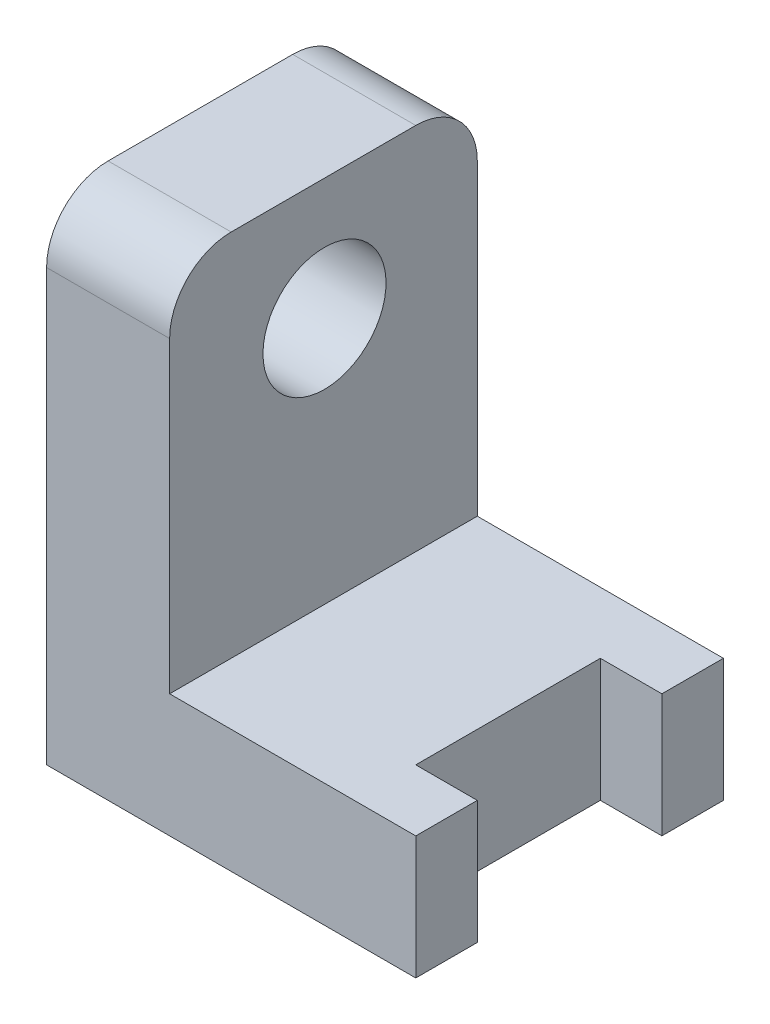
SolidWorks part; units mm, degrees
ref_plane "Piano frontale" through (0, 0, 0) normal (0, 0, 1) x (1, 0, 0)
ref_plane "Piano superiore" through (0, 0, 0) normal (0, 1, 0) x (1, 0, 0)
ref_plane "Piano destro" through (0, 0, 0) normal (1, 0, 0) x (0, 0, -1)
sketch "Schizzo1" plane through (0, 0, 0) normal (0, 0, 1) x (1, 0, 0)
  line L0 (0, 40) -> (0, 0)
  line L1 (0, 0) -> (30, 0)
  line L2 (30, 0) -> (30, 10)
  line L3 (30, 10) -> (10, 10)
  line L4 (10, 10) -> (10, 40)
  line L5 (10, 40) -> (0, 40)
  point P2 (0, 0)
  dimension "D1" = 30
  dimension "D2" = 40
  dimension "D3" = 10
  dimension "D4" = 10
extrude "Estrusione-Estrusione1" add sketch "Schizzo1" along normal mid plane 25
sketch "Schizzo3" plane through (0, 10, 0) normal (0, 1, 0) x (1, 0, 0)
  line L0 (30, 7.5) -> (25, 7.5)
  line L1 (30, -12.5) -> (30, 12.5) construction
  line L2 (25, 7.5) -> (25, -7.5)
  line L3 (25, -7.5) -> (30, -7.5)
  line L4 (30, -7.5) -> (30, 7.5)
  line L5 (0, 0) -> (25, 0) construction
  line L6 (30, 12.5) -> (10, 12.5) construction
  point P9 (0, 0)
  point P10 (25, 7.5132)
  point P15 (24.4725, 0.0815)
  dimension "D1" = 5
  dimension "D2" = 15
  dimension "D3" = 5
extrude "Taglio-Estrusione1" cut sketch "Schizzo3" against normal up to next
hole_wizard "Foro Ø10.0 (10)-1" positions "Schizzo3D3" profile "Schizzo5" hole size "Ø10.0" standard "ISO"
sketch3d "Schizzo3D3"
  line L0 (10, 40, 0) -> (10, 30, 0) construction
  line L1 (10, 40, 12.5) -> (10, 40, -12.5) construction
  line L2 (10, 30, 0) -> (10, 30, 12.5) construction
  line L3 (10, 10, 12.5) -> (10, 40, 12.5) construction
  point P1 (10, 30, 0)
  point P19 (10, 30, 0)
  point P21 (10, 30, 0)
  point P23 (0, 30.1308, -0.0834)
  dimension "D1" = 10
sketch "Schizzo5" plane through (0, 30.1308, -0.0834) normal (0, 1, 0) x (0, 0, 1)
  line L0 (0, 0) -> (0, 10.001)
  line L1 (0, 10.001) -> (5, 10.001)
  line L2 (5, 10.001) -> (5, 0)
  line L5 (5, 0) -> (0, 0)
  line L11 (0, -6.35) -> (0, 107.95) construction
  dimension "Thru Hole Dia." = 10
  dimension "Thru Hole Depth" = 10.001
fillet "Raccordo1" radius 5 2 edges at (5, 40, 12.5) (5, 40, -12.5)
